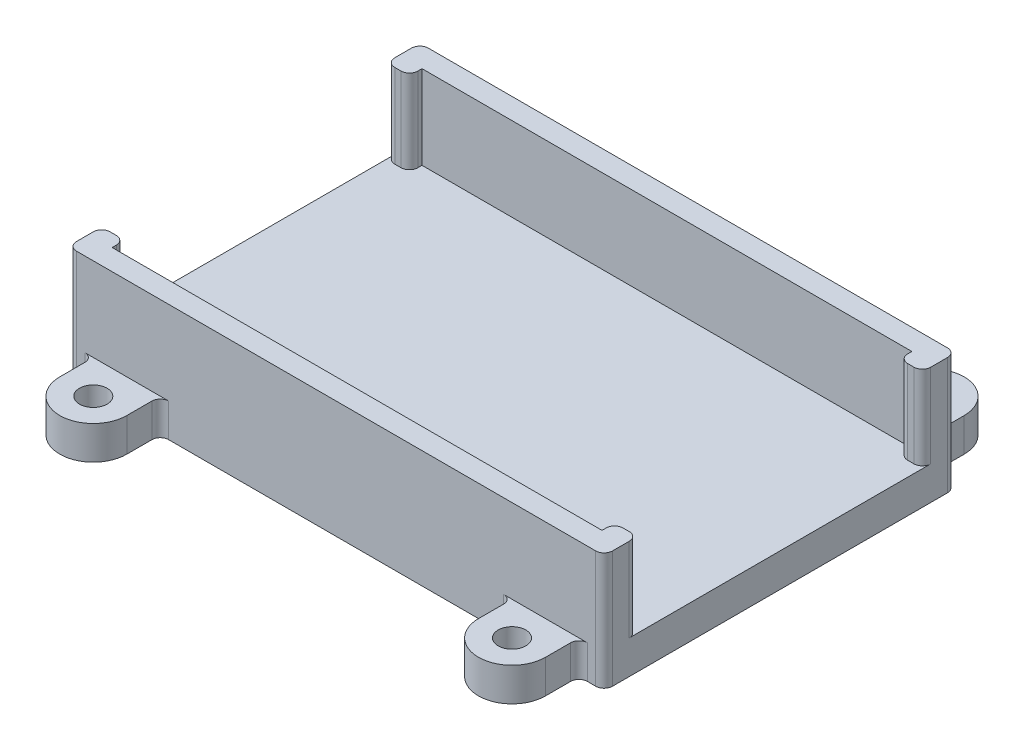
SolidWorks part; units mm, degrees
ref_plane "Front Plane" through (0, 0, 0) normal (0, 0, 1) x (1, 0, 0)
ref_plane "Top Plane" through (0, 0, 0) normal (0, 1, 0) x (1, 0, 0)
ref_plane "Right Plane" through (0, 0, 0) normal (1, 0, 0) x (0, 0, -1)
sketch "Sketch1" plane through (0, 0, 0) normal (0, 1, 0) x (1, 0, 0)
  line L0 (0, -18.5) -> (0, 18.5) construction
  line L1 (-29.25, 0) -> (29.25, 0) construction
  line L2 (-25, 25) -> (25, 25) construction
  line L3 (-29.25, 18.5) -> (29.25, 18.5) construction
  line L4 (-29.25, 18.5) -> (-29.25, -18.5) construction
  line L5 (-29.25, -18.5) -> (29.25, -18.5) construction
  line L6 (29.25, 18.5) -> (29.25, -18.5) construction
  line L7 (-31, 21) -> (-30, 21)
  line L8 (-32, 20) -> (-32, -20)
  line L9 (-31, -21) -> (-30, -21)
  line L10 (32, 20) -> (32, -20)
  line L11 (-25, -25) -> (25, -25) construction
  line L12 (-29, 25) -> (-29, 22)
  line L13 (-21, 25) -> (-21, 22)
  line L14 (-20, 21) -> (20, 21)
  line L15 (29, 25) -> (29, 22)
  line L16 (21, 25) -> (21, 22)
  line L17 (30, 21) -> (31, 21)
  line L18 (29, -25) -> (29, -22)
  line L19 (21, -25) -> (21, -22)
  line L20 (-21, -25) -> (-21, -22)
  line L21 (-29, -25) -> (-29, -22)
  line L22 (-20, -21) -> (20, -21)
  line L23 (30, -21) -> (31, -21)
  arc A0 (-21, 25) -> (-29, 25) centre (-25, 25) ccw
  arc A1 (-32, 20) -> (-31, 21) centre (-31, 20) cw
  arc A2 (-20, 21) -> (-21, 22) centre (-20, 22) cw
  arc A3 (-29, 22) -> (-30, 21) centre (-30, 22) cw
  arc A4 (29, 22) -> (30, 21) centre (30, 22) ccw
  arc A5 (20, 21) -> (21, 22) centre (20, 22) ccw
  arc A6 (21, 25) -> (29, 25) centre (25, 25) cw
  arc A7 (29, -22) -> (30, -21) centre (30, -22) cw
  arc A8 (21, -25) -> (29, -25) centre (25, -25) ccw
  arc A9 (20, -21) -> (21, -22) centre (20, -22) cw
  arc A10 (-20, -21) -> (-21, -22) centre (-20, -22) ccw
  arc A11 (-21, -25) -> (-29, -25) centre (-25, -25) cw
  arc A12 (-29, -22) -> (-30, -21) centre (-30, -22) ccw
  arc A13 (-31, -21) -> (-32, -20) centre (-31, -20) cw
  arc A14 (32, -20) -> (31, -21) centre (31, -20) cw
  arc A15 (32, 20) -> (31, 21) centre (31, 20) ccw
  point P4 (0, 0)
  point P8 (0, 0)
  point P13 (32, 0)
  point P19 (0, 25)
  point P30 (-21, 21)
  point P62 (-25, 29)
  dimension "D9" = 1
  dimension "D10" = 1
  dimension "D1" = 58.5
  dimension "D2" = 37
  dimension "D3" = 64
  dimension "D4" = 42
  dimension "D5" = 2.5
  dimension "D6" = 2.75
  dimension "D7" = 50
  dimension "D8" = 50
  dimension "D11" = 2.75
  dimension "D12" = 42
  dimension "D13" = 8
extrude "Boss-Extrude1" add sketch "Sketch1" along normal blind 14
sketch "Sketch2" plane through (0, 14, 0) normal (0, 1, 0) x (1, 0, 0)
  line L0 (-30, -21) -> (-20, -21)
  line L1 (-29.25, 18.5) -> (29.25, 18.5)
  line L3 (-29.25, -18.5) -> (29.25, -18.5)
  line L4 (29.25, 18.5) -> (29.25, 17)
  line L5 (-29, -25) -> (-29, -22)
  line L6 (-21, -25) -> (-21, -22)
  line L7 (0, 18.5) -> (0, -18.5) construction
  line L8 (21, -25) -> (21, -22)
  line L9 (29, -25) -> (29, -22)
  line L10 (30, -21) -> (20, -21)
  line L11 (0, 0) -> (29.25, 0) construction
  line L12 (30, 21) -> (20, 21)
  line L13 (29, 25) -> (29, 22)
  line L14 (21, 25) -> (21, 22)
  line L15 (-21, 25) -> (-21, 22)
  line L16 (-29, 25) -> (-29, 22)
  line L17 (-30, 21) -> (-20, 21)
  line L18 (29.25, 17) -> (32, 17)
  line L19 (32, -20) -> (32, 20) construction
  line L21 (32, -17) -> (29.25, -17)
  line L22 (29.25, -17) -> (29.25, -18.5)
  line L23 (32, 17) -> (32, -17)
  line L24 (32, 0) -> (29.25, 0) construction
  line L25 (-29.25, -17) -> (-29.25, -18.5)
  line L26 (-32, -17) -> (-29.25, -17)
  line L27 (-32, 17) -> (-32, -17)
  line L28 (-29.25, 17) -> (-32, 17)
  line L29 (-29.25, 18.5) -> (-29.25, 17)
  line L30 (-32, 20) -> (-32, -20) construction
  arc A0 (-29, -25) -> (-21, -25) centre (-25, -25) ccw
  arc A1 (-30, -21) -> (-29, -22) centre (-30, -22) cw
  arc A2 (-20, -21) -> (-21, -22) centre (-20, -22) ccw
  arc A3 (20, -21) -> (21, -22) centre (20, -22) cw
  arc A4 (30, -21) -> (29, -22) centre (30, -22) ccw
  arc A5 (29, -25) -> (21, -25) centre (25, -25) cw
  arc A6 (29, 25) -> (21, 25) centre (25, 25) ccw
  arc A7 (30, 21) -> (29, 22) centre (30, 22) cw
  arc A8 (20, 21) -> (21, 22) centre (20, 22) ccw
  arc A9 (-20, 21) -> (-21, 22) centre (-20, 22) cw
  arc A10 (-30, 21) -> (-29, 22) centre (-30, 22) ccw
  arc A11 (-29, 25) -> (-21, 25) centre (-25, 25) cw
  dimension "D1" = 1
  dimension "D2" = 1
  dimension "D3" = 90
  dimension "D4" = 17
  dimension "D5" = 2.5
  dimension "D6" = 2.75
extrude "Cut-Extrude1" cut sketch "Sketch2" against normal blind 10
hole_wizard "M4x0.7 Tapped Hole1" positions "Sketch3" profile "Sketch4" tap size "M4x0.7" standard "ANSI Metric" end condition through all
sketch "Sketch3" plane through (0, 4, 0) normal (0, 1, 0) x (1, 0, 0)
  point P0 (-25, 25)
  point P3 (25, 25)
  point P6 (25, -25)
  point P9 (-25, -25)
sketch "Sketch4" plane through (-25, 4, -25) normal (1, 0, 0) x (0, 0, 1)
  line L0 (0, 0) -> (0, 4)
  line L1 (0, 4) -> (1.65, 4)
  line L2 (1.65, 4) -> (1.65, 0)
  line L5 (1.65, 0) -> (0, 0)
  line L11 (0, -6.35) -> (0, 107.95) construction
  dimension "Thru Tap Drill Dia." = 3.3
  dimension "Thru Tap Drill Depth" = 4
cosmetic thread "Hole Thread1" parameters "D2"=4
cosmetic thread "Hole Thread2" parameters "D2"=4
cosmetic thread "Hole Thread3" parameters "D2"=4
cosmetic thread "Hole Thread4" parameters "D2"=4
ref_plane "Plane1" through (-14.25, 0, 0) normal (1, 0, 0) x (0, 0, -1)
sketch "Sketch7" plane through (-14.25, 0, 0) normal (1, 0, 0) x (0, 0, -1)
  line L0 (-21, 12) -> (-19.5, 12)
  line L1 (-21, 14) -> (-21, 0) construction
  line L2 (-19.5, 12) -> (-19.5, 11)
  line L3 (-19.5, 11) -> (-21, 8.5)
  line L4 (-21, 8.5) -> (-21, 12)
  line L5 (-20, 14) -> (-21, 14) construction
  dimension "D1" = 1.5
  dimension "D2" = 3.5
  dimension "D3" = 1
  dimension "D4" = 2
fillet "Fillet2" radius 1 8 edges at (29.25, 9, 17) (29.25, 9, -17) (32, 9, 17) (32, 9, -17) (-29.25, 9, 17) (-32, 9, 17) (-29.25, 9, -17) (-32, 9, -17)
